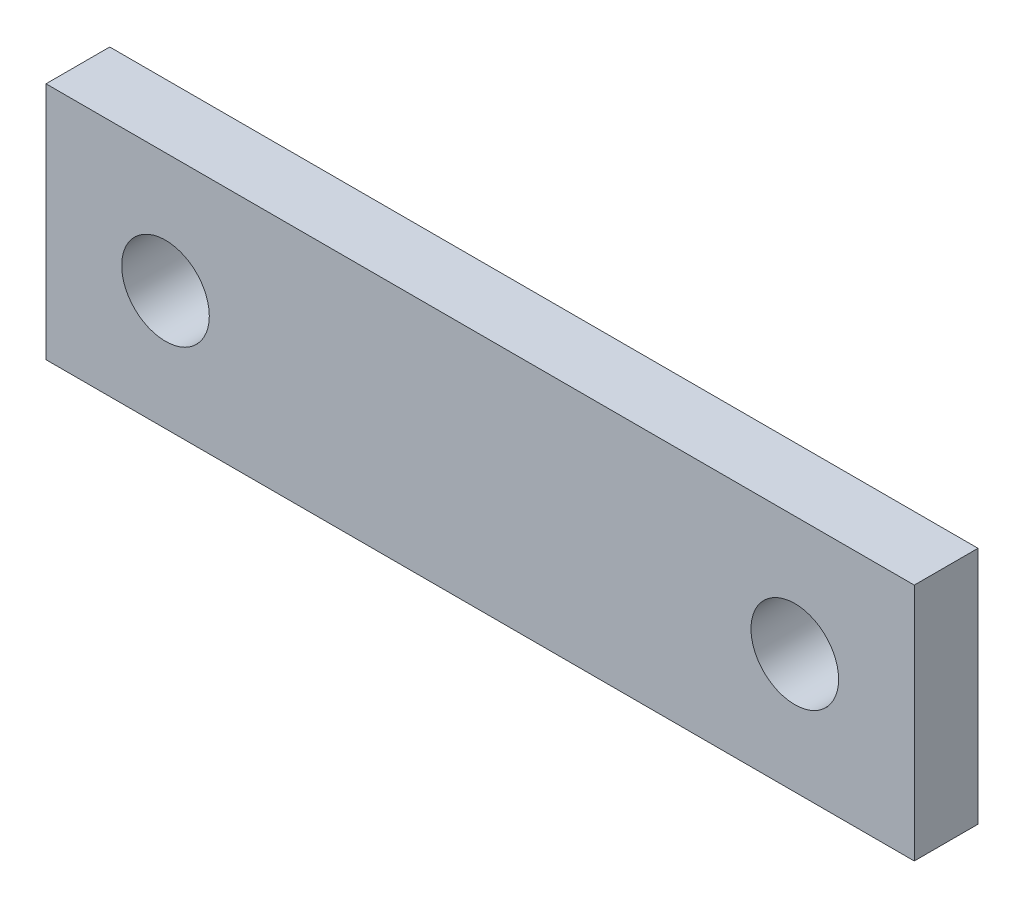
SolidWorks part; units mm, degrees
ref_plane "前视基准面" through (0, 0, 0) normal (0, 0, 1) x (1, 0, 0)
ref_plane "上视基准面" through (0, 0, 0) normal (0, 1, 0) x (1, 0, 0)
ref_plane "右视基准面" through (0, 0, 0) normal (1, 0, 0) x (0, 0, -1)
sketch "草图1" plane through (0, 0, 0) normal (0, 0, 1) x (1, 0, 0)
  line L1 (0, 0) -> (218, 0)
  line L2 (0, 0) -> (0, 60)
  line L3 (0, 60) -> (218, 60)
  line L4 (218, 0) -> (218, 60)
  dimension "D1" = 218
  dimension "D2" = 60
extrude "拉伸1" add sketch "草图1" along normal blind 16
sketch "草图2" plane through (0, 0, 16) normal (0, 0, 1) x (1, 0, 0)
  line L0 (0, 30) -> (218, 30) construction
  line L1 (0, 60) -> (0, 0) construction
  line L2 (218, 0) -> (218, 60) construction
  line L3 (109, 60) -> (109, 0) construction
  line L4 (218, 60) -> (0, 60) construction
  line L5 (0, 0) -> (218, 0) construction
  circle A0 centre (30, 30) radius 11
  circle A1 centre (188, 30) radius 11
  dimension "D3" = 22
  dimension "D1" = 79
  dimension "D2" = 158
extrude "拉伸2" cut sketch "草图2" against normal through all
